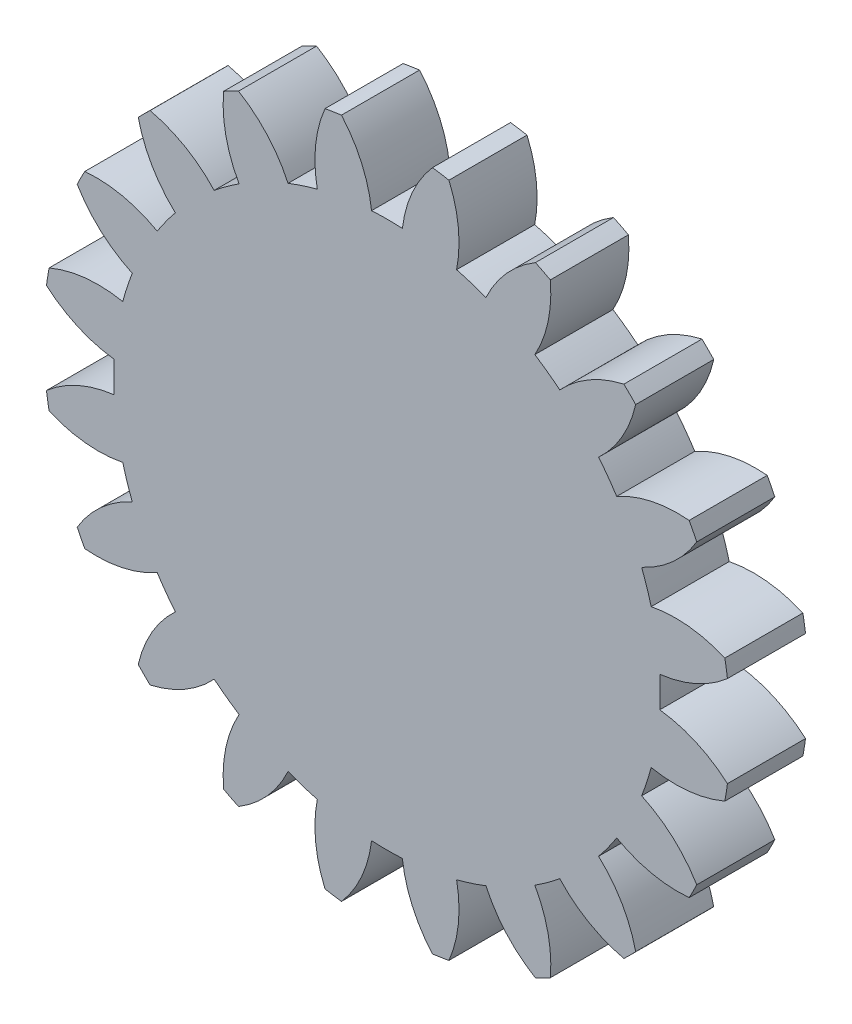
SolidWorks part; units mm, degrees
ref_plane "Front Plane" through (0, 0, 0) normal (0, 0, 1) x (1, 0, 0)
ref_plane "Top Plane" through (0, 0, 0) normal (0, 1, 0) x (1, 0, 0)
ref_plane "Right Plane" through (0, 0, 0) normal (1, 0, 0) x (0, 0, -1)
sketch "Sketch1" plane through (0, 0, 0) normal (0, 0, 1) x (1, 0, 0)
  arc A0 (-21.8063, 2.9127) -> (-17.4712, 0.9862) centre (-16.536, 8.9313) ccw
  arc A1 (-17.4712, 0.9862) -> (-17.4712, -0.9862) centre (0, 0) ccw
  arc A2 (-17.4712, -0.9862) -> (-21.8063, -2.9127) centre (-16.536, -8.9313) ccw
  arc A3 (-21.8063, -2.9127) -> (-21.6391, -3.9684) centre (0, 0) ccw
  arc A4 (-21.6391, -3.9684) -> (-16.9208, -4.461) centre (-18.4866, 3.3843) ccw
  arc A5 (-16.9208, -4.461) -> (-16.3113, -6.3368) centre (0, 0) ccw
  arc A6 (-16.3113, -6.3368) -> (-19.839, -9.5087) centre (-12.9668, -13.6041) ccw
  arc A7 (-19.839, -9.5087) -> (-19.3537, -10.461) centre (0, 0) ccw
  arc A8 (-19.3537, -10.461) -> (-14.7141, -9.4715) centre (-18.6276, -2.494) ccw
  arc A9 (-14.7141, -9.4715) -> (-13.5548, -11.0671) centre (0, 0) ccw
  arc A10 (-13.5548, -11.0671) -> (-15.9297, -15.1739) centre (-8.1282, -16.9452) ccw
  arc A11 (-15.9297, -15.1739) -> (-15.1739, -15.9297) centre (0, 0) ccw
  arc A12 (-15.1739, -15.9297) -> (-11.0671, -13.5548) centre (-16.9452, -8.1282) ccw
  arc A13 (-11.0671, -13.5548) -> (-9.4715, -14.7141) centre (0, 0) ccw
  arc A14 (-9.4715, -14.7141) -> (-10.461, -19.3537) centre (-2.494, -18.6276) ccw
  arc A15 (-10.461, -19.3537) -> (-9.5087, -19.839) centre (0, 0) ccw
  arc A16 (-9.5087, -19.839) -> (-6.3368, -16.3113) centre (-13.6041, -12.9668) ccw
  arc A17 (-6.3368, -16.3113) -> (-4.461, -16.9208) centre (0, 0) ccw
  arc A18 (-4.461, -16.9208) -> (-3.9684, -21.6391) centre (3.3843, -18.4866) ccw
  arc A19 (-3.9684, -21.6391) -> (-2.9127, -21.8063) centre (0, 0) ccw
  arc A20 (-2.9127, -21.8063) -> (-0.9862, -17.4712) centre (-8.9313, -16.536) ccw
  arc A21 (-0.9862, -17.4712) -> (0.9862, -17.4712) centre (0, 0) ccw
  arc A22 (0.9862, -17.4712) -> (2.9127, -21.8063) centre (8.9313, -16.536) ccw
  arc A23 (2.9127, -21.8063) -> (3.9684, -21.6391) centre (0, 0) ccw
  arc A24 (3.9684, -21.6391) -> (4.461, -16.9208) centre (-3.3843, -18.4866) ccw
  arc A25 (4.461, -16.9208) -> (6.3368, -16.3113) centre (0, 0) ccw
  arc A26 (6.3368, -16.3113) -> (9.5087, -19.839) centre (13.6041, -12.9668) ccw
  arc A27 (9.5087, -19.839) -> (10.461, -19.3537) centre (0, 0) ccw
  arc A28 (10.461, -19.3537) -> (9.4715, -14.7141) centre (2.494, -18.6276) ccw
  arc A29 (9.4715, -14.7141) -> (11.0671, -13.5548) centre (0, 0) ccw
  arc A30 (11.0671, -13.5548) -> (15.1739, -15.9297) centre (16.9452, -8.1282) ccw
  arc A31 (15.1739, -15.9297) -> (15.9297, -15.1739) centre (0, 0) ccw
  arc A32 (15.9297, -15.1739) -> (13.5548, -11.0671) centre (8.1282, -16.9452) ccw
  arc A33 (13.5548, -11.0671) -> (14.7141, -9.4715) centre (0, 0) ccw
  arc A34 (14.7141, -9.4715) -> (19.3537, -10.461) centre (18.6276, -2.494) ccw
  arc A35 (19.3537, -10.461) -> (19.839, -9.5087) centre (0, 0) ccw
  arc A36 (19.839, -9.5087) -> (16.3113, -6.3368) centre (12.9668, -13.6041) ccw
  arc A37 (16.3113, -6.3368) -> (16.9208, -4.461) centre (0, 0) ccw
  arc A38 (16.9208, -4.461) -> (21.6391, -3.9684) centre (18.4866, 3.3843) ccw
  arc A39 (21.6391, -3.9684) -> (21.8063, -2.9127) centre (0, 0) ccw
  arc A40 (21.8063, -2.9127) -> (17.4712, -0.9862) centre (16.536, -8.9313) ccw
  arc A41 (17.4712, -0.9862) -> (17.4712, 0.9862) centre (0, 0) ccw
  arc A42 (17.4712, 0.9862) -> (21.8063, 2.9127) centre (16.536, 8.9313) ccw
  arc A43 (21.8063, 2.9127) -> (21.6391, 3.9684) centre (0, 0) ccw
  arc A44 (21.6391, 3.9684) -> (16.9208, 4.461) centre (18.4866, -3.3843) ccw
  arc A45 (16.9208, 4.461) -> (16.3113, 6.3368) centre (0, 0) ccw
  arc A46 (16.3113, 6.3368) -> (19.839, 9.5087) centre (12.9668, 13.6041) ccw
  arc A47 (19.839, 9.5087) -> (19.3537, 10.461) centre (0, 0) ccw
  arc A48 (19.3537, 10.461) -> (14.7141, 9.4715) centre (18.6276, 2.494) ccw
  arc A49 (14.7141, 9.4715) -> (13.5548, 11.0671) centre (0, 0) ccw
  arc A50 (13.5548, 11.0671) -> (15.9297, 15.1739) centre (8.1282, 16.9452) ccw
  arc A51 (15.9297, 15.1739) -> (15.1739, 15.9297) centre (0, 0) ccw
  arc A52 (15.1739, 15.9297) -> (11.0671, 13.5548) centre (16.9452, 8.1282) ccw
  arc A53 (11.0671, 13.5548) -> (9.4715, 14.7141) centre (0, 0) ccw
  arc A54 (9.4715, 14.7141) -> (10.461, 19.3537) centre (2.494, 18.6276) ccw
  arc A55 (10.461, 19.3537) -> (9.5087, 19.839) centre (0, 0) ccw
  arc A56 (9.5087, 19.839) -> (6.3368, 16.3113) centre (13.6041, 12.9668) ccw
  arc A57 (6.3368, 16.3113) -> (4.461, 16.9208) centre (0, 0) ccw
  arc A58 (4.461, 16.9208) -> (3.9684, 21.6391) centre (-3.3843, 18.4866) ccw
  arc A59 (3.9684, 21.6391) -> (2.9127, 21.8063) centre (0, 0) ccw
  arc A60 (2.9127, 21.8063) -> (0.9862, 17.4712) centre (8.9313, 16.536) ccw
  arc A61 (0.9862, 17.4712) -> (-0.9862, 17.4712) centre (0, 0) ccw
  arc A62 (-0.9862, 17.4712) -> (-2.9127, 21.8063) centre (-8.9313, 16.536) ccw
  arc A63 (-2.9127, 21.8063) -> (-3.9684, 21.6391) centre (0, 0) ccw
  arc A64 (-3.9684, 21.6391) -> (-4.461, 16.9208) centre (3.3843, 18.4866) ccw
  arc A65 (-4.461, 16.9208) -> (-6.3368, 16.3113) centre (0, 0) ccw
  arc A66 (-6.3368, 16.3113) -> (-9.5087, 19.839) centre (-13.6041, 12.9668) ccw
  arc A67 (-9.5087, 19.839) -> (-10.461, 19.3537) centre (0, 0) ccw
  arc A68 (-10.461, 19.3537) -> (-9.4715, 14.7141) centre (-2.494, 18.6276) ccw
  arc A69 (-9.4715, 14.7141) -> (-11.0671, 13.5548) centre (0, 0) ccw
  arc A70 (-11.0671, 13.5548) -> (-15.1739, 15.9297) centre (-16.9452, 8.1282) ccw
  arc A71 (-15.1739, 15.9297) -> (-15.9297, 15.1739) centre (0, 0) ccw
  arc A72 (-15.9297, 15.1739) -> (-13.5548, 11.0671) centre (-8.1282, 16.9452) ccw
  arc A73 (-13.5548, 11.0671) -> (-14.7141, 9.4715) centre (0, 0) ccw
  arc A74 (-14.7141, 9.4715) -> (-19.3537, 10.461) centre (-18.6276, 2.494) ccw
  arc A75 (-19.3537, 10.461) -> (-19.839, 9.5087) centre (0, 0) ccw
  arc A76 (-19.839, 9.5087) -> (-16.3113, 6.3368) centre (-12.9668, 13.6041) ccw
  arc A77 (-16.3113, 6.3368) -> (-16.9208, 4.461) centre (0, 0) ccw
  arc A78 (-16.9208, 4.461) -> (-21.6391, 3.9684) centre (-18.4866, -3.3843) ccw
  arc A79 (-21.6391, 3.9684) -> (-21.8063, 2.9127) centre (0, 0) ccw
extrude "Boss-Extrude1" add sketch "Sketch1" along normal blind 5
